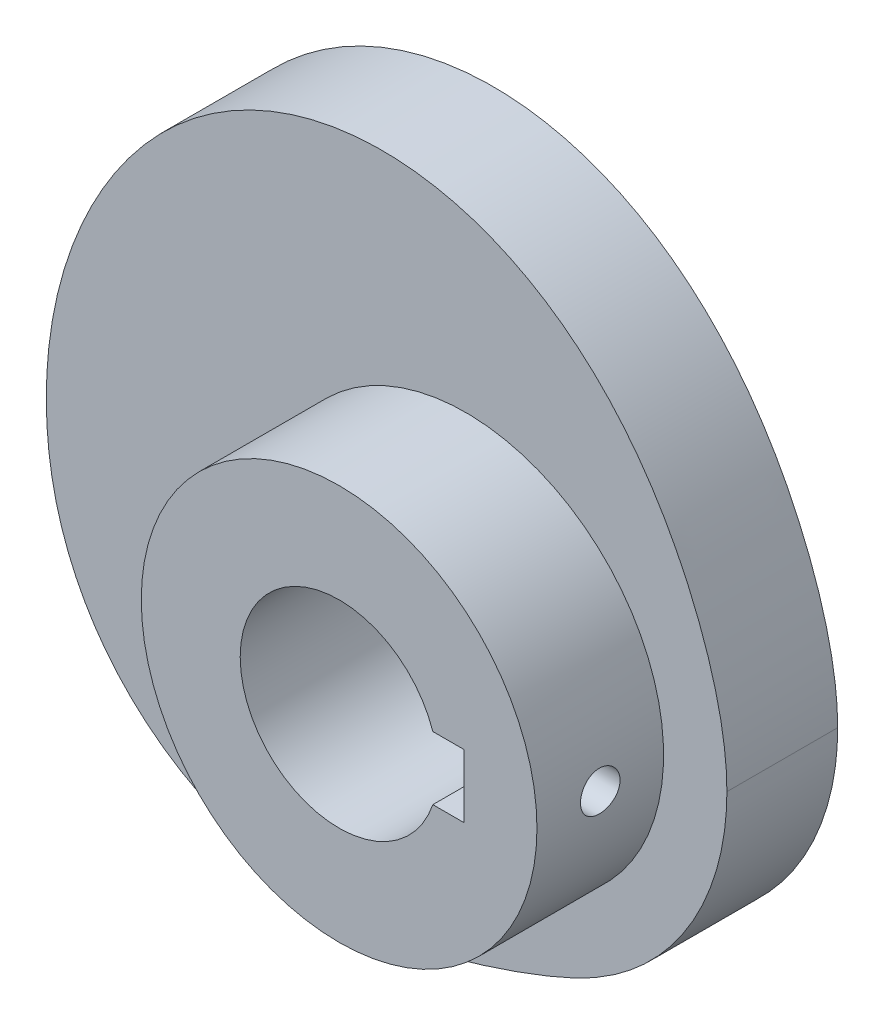
SolidWorks part; units mm, degrees
ref_plane "前视基准面" through (0, 0, 0) normal (0, 0, 1) x (1, 0, 0)
ref_plane "上视基准面" through (0, 0, 0) normal (0, 1, 0) x (1, 0, 0)
ref_plane "右视基准面" through (0, 0, 0) normal (1, 0, 0) x (0, 0, -1)
sketch "草图1" plane through (0, 0, 0) normal (0, 0, 1) x (1, 0, 0)
  spline S0 degree 3 poles (33, 0) (32.9947, 0.45) (32.9841, 1.3502) (32.9011, 2.6987) (32.7729, 4.0439) (32.5973, 5.385) (32.3786, 6.7212) (32.0321, 8.4983) (31.5017, 10.7105) (30.7267, 13.3474) (29.8204, 15.9783) (28.7838, 18.6117) (27.6103, 21.2543) (26.5152, 23.451) (25.5575, 25.2113) (24.789, 26.5427) (23.9727, 27.8741) (23.1055, 29.2037) (22.1844, 30.5287) (21.2066, 31.8461) (20.1692, 33.1521) (19.0698, 34.4427) (17.9061, 35.713) (16.6761, 36.9579) (15.3786, 38.1717) (14.0127, 39.3486) (12.5779, 40.4822) (11.0745, 41.5661) (9.5035, 42.5938) (7.8665, 43.5584) (6.1656, 44.4534) (4.4039, 45.2722) (2.5849, 46.0086) (0.7129, 46.6564) (-1.2072, 47.2102) (-3.17, 47.6645) (-5.1696, 48.0148) (-7.1995, 48.257) (-9.2529, 48.3877) (-11.3227, 48.4039) (-13.4016, 48.3038) (-15.4821, 48.086) (-17.5567, 47.7499) (-19.6178, 47.2959) (-21.6581, 46.7247) (-23.6703, 46.0382) (-25.6477, 45.2386) (-27.5837, 44.3289) (-29.4721, 43.3128) (-31.3074, 42.1944) (-33.0845, 40.9781) (-34.7987, 39.669) (-36.4463, 38.2723) (-38.0239, 36.7934) (-39.5289, 35.238) (-40.9591, 33.6116) (-42.3135, 31.9201) (-43.5893, 30.168) (-44.7933, 28.3646) (-45.5306, 27.1216) (-45.8993, 26.5) knots 0 0 0 0 0.011721 0.023445 0.035174 0.046913 0.058664 0.070435 0.094064 0.117884 0.141995 0.166516 0.191572 0.217284 0.230421 0.243762 0.257317 0.271094 0.2851 0.299341 0.313818 0.328534 0.343489 0.358679 0.374103 0.389754 0.405627 0.421715 0.43801 0.454504 0.471186 0.488049 0.505082 0.522276 0.539621 0.557107 0.574726 0.592468 0.610326 0.62829 0.646352 0.664507 0.682745 0.701061 0.719448 0.7379 0.756411 0.774974 0.793585 0.812237 0.830926 0.849646 0.868392 0.88716 0.905945 0.924742 0.943549 0.962362 0.98118 1 1 1 1
  spline S1 degree 3 poles (-45.8993, 26.5) (-46.1837, 25.9966) (-46.7524, 24.9898) (-47.5422, 23.4451) (-48.2846, 21.8775) (-48.9743, 20.2858) (-49.6119, 18.6726) (-50.1963, 17.0393) (-50.7269, 15.3878) (-51.2032, 13.7199) (-51.6247, 12.0372) (-51.9909, 10.3416) (-52.3014, 8.635) (-52.5559, 6.9191) (-52.7544, 5.1958) (-52.8953, 3.467) (-52.9836, 1.7344) (-52.9945, 0.5781) (-53, 0) knots 0 0 0 0 0.0625 0.125 0.1875 0.25 0.3125 0.375 0.4375 0.5 0.5625 0.625 0.6875 0.75 0.8125 0.875 0.9375 1 1 1 1
  spline S2 degree 3 poles (-53, 0) (-52.9945, -0.5781) (-52.9836, -1.734) (-52.8909, -3.4657) (-52.7375, -5.1922) (-52.5148, -6.9104) (-52.2218, -8.6169) (-51.8558, -10.3079) (-51.4154, -11.9794) (-50.8998, -13.6272) (-50.3086, -15.247) (-49.6419, -16.8344) (-48.9005, -18.3851) (-48.0857, -19.8948) (-47.1992, -21.3594) (-46.2434, -22.7749) (-45.221, -24.1375) (-44.135, -25.4438) (-42.9888, -26.6905) (-41.7864, -27.8747) (-40.5318, -28.994) (-39.2293, -30.0462) (-37.8834, -31.0295) (-36.4988, -31.9427) (-35.0803, -32.7847) (-33.6326, -33.5551) (-32.1607, -34.2539) (-30.6693, -34.8813) (-29.1631, -35.438) (-27.6468, -35.9252) (-26.1248, -36.3444) (-24.6013, -36.6974) (-23.0805, -36.9864) (-21.5662, -37.2138) (-20.0617, -37.3824) (-18.5704, -37.4951) (-17.095, -37.555) (-15.6383, -37.5655) (-14.2023, -37.5299) (-12.7888, -37.4518) (-11.3994, -37.3347) (-9.5949, -37.1329) (-7.4035, -36.8026) (-4.8577, -36.3015) (-2.4137, -35.7228) (-0.0646, -35.087) (2.1999, -34.4096) (4.3915, -33.701) (6.5226, -32.9653) (8.6038, -32.2004) (10.6436, -31.3987) (12.6436, -30.5428) (14.607, -29.6247) (15.8694, -28.9273) (16.5, -28.5788) knots 0 0 0 0 0.018617 0.03723 0.055835 0.074432 0.093016 0.111587 0.130139 0.14867 0.167177 0.185656 0.204103 0.222515 0.240888 0.259219 0.277503 0.295734 0.31391 0.332023 0.350069 0.36804 0.385931 0.403734 0.42144 0.439043 0.456533 0.473901 0.491139 0.508236 0.525183 0.54197 0.558589 0.575028 0.591281 0.607336 0.623188 0.638828 0.654249 0.669446 0.684415 0.699152 0.727922 0.755761 0.782701 0.808797 0.834134 0.858819 0.882978 0.906741 0.930232 0.95356 0.976801 1 1 1 1
  spline S3 degree 3 poles (16.5, -28.5788) (17.1167, -28.2071) (18.3501, -27.4636) (20.1026, -26.1979) (21.7742, -24.8288) (23.3511, -23.3511) (24.8285, -21.774) (26.1994, -20.1035) (27.4581, -18.3469) (28.5992, -16.5118) (29.6179, -14.606) (30.5098, -12.6376) (31.271, -10.6151) (31.8982, -8.5471) (32.3895, -6.4426) (32.7394, -4.3104) (32.9592, -2.1598) (32.9864, -0.7199) (33, 0) knots 0 0 0 0 0.0625 0.125 0.1875 0.25 0.3125 0.375 0.4375 0.5 0.5625 0.625 0.6875 0.75 0.8125 0.875 0.9375 1 1 1 1
extrude "凸台-拉伸1" add sketch "草图1" along normal blind 14
sketch "草图2" plane through (0, 0, 0) normal (0, 0, 1) x (1, 0, 0)
  circle A0 centre (0, 0) radius 25
extrude "凸台-拉伸2" add sketch "草图2" along normal blind 30
sketch "草图3" plane through (0, 0, 0) normal (0, 0, 1) x (1, 0, 0)
  circle A0 centre (0, 0) radius 12.5
extrude "切除-拉伸1" cut sketch "草图3" along normal through all
sketch "草图4" plane through (0, 0, 0) normal (0, 0, 1) x (1, 0, 0)
  line L0 (0, -4) -> (15.8, -4)
  line L1 (15.8, -4) -> (15.8, 4)
  line L2 (15.8, 4) -> (0, 4)
  line L3 (0, 4) -> (0, -4)
extrude "切除-拉伸2" cut sketch "草图4" along normal through all
sketch3d "3D草图1"
  line L0 (-1, 0, 22) -> (26, 0, 22)
sweep "切除-扫描2" cut path "3D草图1" circular profile diameter 5 parameters "D3"=5
